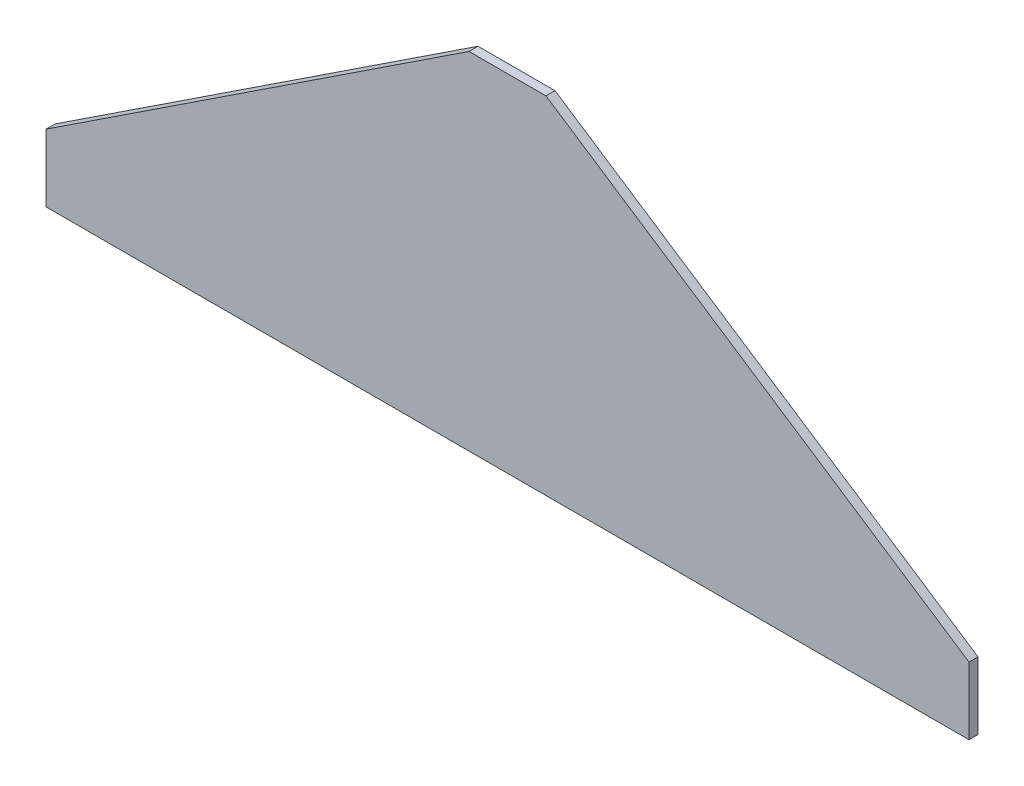
SolidWorks part; units mm, degrees
material "Pine"
ref_plane "Front Plane" through (0, 0, 0) normal (0, 0, 1) x (1, 0, 0)
ref_plane "Top Plane" through (0, 0, 0) normal (0, 1, 0) x (1, 0, 0)
ref_plane "Right Plane" through (0, 0, 0) normal (1, 0, 0) x (0, 0, -1)
sketch "Sketch1" plane through (0, 0, 0) normal (0, 0, 1) x (1, 0, 0)
  line L1 (-609.6, -228.6) -> (609.6, -228.6)
  line L2 (-609.6, -228.6) -> (-609.6, 228.6)
  line L3 (-609.6, 228.6) -> (609.6, 228.6)
  line L4 (609.6, -228.6) -> (609.6, 228.6)
  line L5 (-609.6, -228.6) -> (609.6, 228.6) construction
  line L6 (-609.6, 228.6) -> (609.6, -228.6) construction
  point P1 (0, 0)
  dimension "D1" = 457.2
  dimension "D2" = 1219.2
extrude "Boss-Extrude1" add sketch "Sketch1" along normal blind 11.9062
chamfer "Chamfer1" distance 368.3 distance2 558.8 2 edges at (609.6, 228.6, 5.9531) (-609.6, 228.6, 5.9531)
